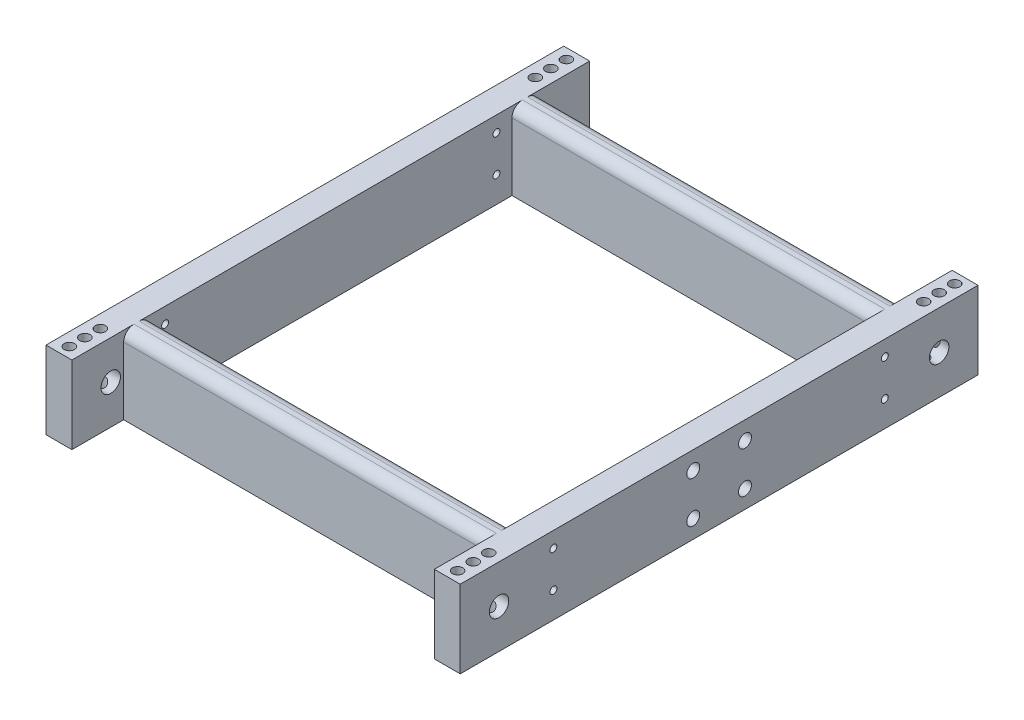
SolidWorks part; units mm, degrees
ref_plane "Front Plane" through (0, 0, 0) normal (0, 0, 1) x (1, 0, 0)
ref_plane "Top Plane" through (0, 0, 0) normal (0, 1, 0) x (1, 0, 0)
ref_plane "Right Plane" through (0, 0, 0) normal (1, 0, 0) x (0, 0, -1)
sketch "Sketch1" plane through (0, 0, 0) normal (0, 1, 0) x (1, 0, 0)
  line L0 (88.9, 101.6) -> (88.9, 127)
  line L1 (-88.9, -101.6) -> (88.9, -101.6)
  line L2 (-101.6, -88.9) -> (-101.6, 88.9)
  line L3 (-88.9, 101.6) -> (88.9, 101.6)
  line L4 (101.6, -88.9) -> (101.6, 88.9)
  line L5 (-101.6, -88.9) -> (101.6, 88.9) construction
  line L6 (-101.6, 88.9) -> (101.6, -88.9) construction
  line L7 (-88.9, 88.9) -> (88.9, 88.9)
  line L8 (-88.9, 88.9) -> (-88.9, -88.9)
  line L9 (-88.9, -88.9) -> (88.9, -88.9)
  line L10 (88.9, 88.9) -> (88.9, -88.9)
  line L11 (-88.9, 88.9) -> (88.9, -88.9) construction
  line L12 (-88.9, -88.9) -> (88.9, 88.9) construction
  line L13 (88.9, 127) -> (101.6, 127)
  line L14 (101.6, 127) -> (101.6, 88.9)
  line L15 (0, 0) -> (0, 88.9) construction
  line L16 (-101.6, 127) -> (-101.6, 88.9)
  line L17 (-88.9, 127) -> (-101.6, 127)
  line L18 (-88.9, 101.6) -> (-88.9, 127)
  line L19 (0, 0) -> (88.9, 0) construction
  line L20 (-88.9, -101.6) -> (-88.9, -127)
  line L21 (-88.9, -127) -> (-101.6, -127)
  line L22 (-101.6, -127) -> (-101.6, -88.9)
  line L23 (101.6, -127) -> (101.6, -88.9)
  line L24 (88.9, -127) -> (101.6, -127)
  line L25 (88.9, -101.6) -> (88.9, -127)
  line L26 (-88.9, 114.3) -> (-101.6, 114.3) construction
  circle A0 centre (-95.25, 114.3) radius 2.54
  circle A8 centre (95.25, 114.3) radius 2.54
  circle A9 centre (95.25, -114.3) radius 2.54
  circle A10 centre (-95.25, -114.3) radius 2.54
  circle A11 centre (-95.25, 121.92) radius 2.54
  circle A12 centre (-95.25, 106.68) radius 2.54
  circle A13 centre (95.25, 106.68) radius 2.54
  circle A14 centre (95.25, 121.92) radius 2.54
  circle A15 centre (95.25, -106.68) radius 2.54
  circle A16 centre (95.25, -121.92) radius 2.54
  circle A17 centre (-95.25, -121.92) radius 2.54
  circle A18 centre (-95.25, -106.68) radius 2.54
  point P0 (0, 0)
  point P6 (0, 0)
  point P32 (-95.25, 127)
  dimension "D7" = 5.08
  dimension "D1" = 7.62
  dimension "D2" = 203.2
  dimension "D3" = 12.7
  dimension "D4" = 12.7
  dimension "D5" = 25.4
  dimension "D6" = 203.2
extrude "Boss-Extrude1" add sketch "Sketch1" along normal blind 38.1
sketch "Sketch2" plane through (-101.6, 0, 0) normal (-1, 0, 0) x (0, 0, 1)
  line L0 (0, 0) -> (0, 38.1) construction
  line L1 (-127, 38.1) -> (127, 38.1) construction
  line L2 (-127, 38.1) -> (-127, 0) construction
  circle A0 centre (-107.95, 19.147) radius 4.7625
  circle A1 centre (107.95, 19.147) radius 4.7625
  circle A2 centre (-81.28, 30.48) radius 1.7
  circle A3 centre (-81.28, 12.7) radius 1.7
  circle A4 centre (81.28, 12.7) radius 1.7
  circle A5 centre (81.28, 30.48) radius 1.7
  dimension "D1" = 9.525
  dimension "D4" = 3.4
  dimension "D2" = 19.05
  dimension "D3" = 18.953
  dimension "D5" = 7.62
  dimension "D6" = 17.78
  dimension "D7" = 81.28
extrude "Cut-Extrude1" cut sketch "Sketch2" against normal blind 443.23
sketch "Sketch4" plane through (101.6, 0, 0) normal (1, 0, 0) x (0, 0, -1)
  line L0 (0, 38.1) -> (0, 0) construction
  line L1 (-127, 38.1) -> (127, 38.1) construction
  line L2 (0, 19.05) -> (-127, 19.05) construction
  line L3 (-127, 38.1) -> (-127, 0) construction
  circle A1 centre (-12.7, 8.89) radius 3.175
  circle A2 centre (12.7, 8.89) radius 3.175
  circle A4 centre (12.7, 29.21) radius 3.175
  circle A5 centre (-12.7, 29.21) radius 3.175
  dimension "D1" = 6.35
  dimension "D2" = 10.16
  dimension "D3" = 12.7
extrude "Cut-Extrude2" cut sketch "Sketch4" against normal blind 22.606
fillet "Fillet1" radius 5.08 4 edges at (0, 38.1, 88.9) (0, 38.1, 101.6) (0, 38.1, -101.6) (0, 38.1, -88.9)
